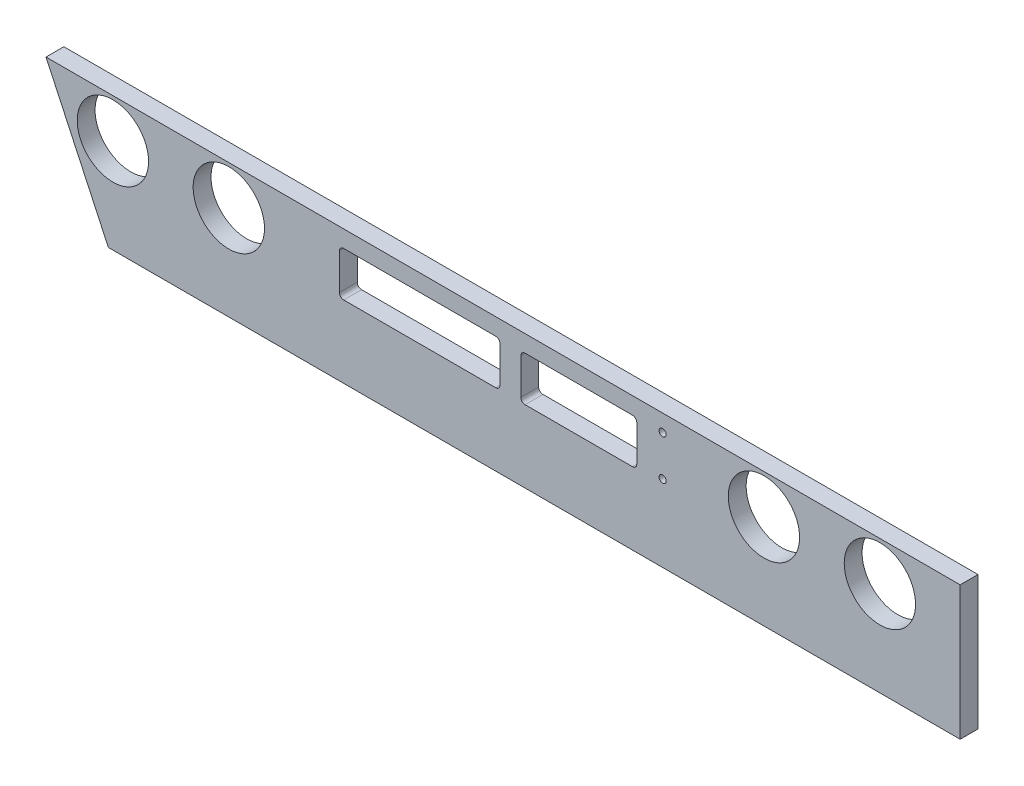
SolidWorks part; units mm, degrees
ref_plane "front" through (0, 0, 0) normal (0, 0, 1) x (1, 0, 0)
ref_plane "top" through (0, 0, 0) normal (0, 1, 0) x (1, 0, 0)
ref_plane "right" through (0, 0, 0) normal (1, 0, 0) x (0, 0, -1)
sketch "Sketch1" plane through (0, 0, 0) normal (0, 0, 1) x (1, 0, 0)
  line L0 (0, 0) -> (0, -90.9256) construction
  line L1 (-165.1, 23.8125) -> (165.1, 23.8125)
  line L2 (-165.1, 23.8125) -> (-165.1, -23.8125)
  line L3 (-165.1, -23.8125) -> (165.1, -23.8125)
  line L4 (165.1, 23.8125) -> (165.1, -23.8125)
  line L6 (-54.356, 17.78) -> (-0.254, 17.78)
  line L7 (-55.88, 16.256) -> (-55.88, 3.429)
  line L8 (-54.356, 1.905) -> (-0.254, 1.905)
  line L9 (1.27, 16.256) -> (1.27, 3.429)
  line L10 (10.2235, 17.78) -> (48.4505, 17.78)
  line L11 (8.6995, 16.256) -> (8.6995, 3.429)
  line L12 (10.2235, 1.905) -> (48.4505, 1.905)
  line L13 (49.9745, 16.256) -> (49.9745, 3.429)
  circle A0 centre (-136.525, 9.8425) radius 12.7
  circle A1 centre (-95.25, 9.8425) radius 12.7
  circle A2 centre (95.25, 9.8425) radius 12.7
  circle A3 centre (136.525, 9.8425) radius 12.7
  arc A4 (-54.356, 17.78) -> (-55.88, 16.256) centre (-54.356, 16.256) ccw
  arc A5 (-55.88, 3.429) -> (-54.356, 1.905) centre (-54.356, 3.429) ccw
  arc A6 (-0.254, 1.905) -> (1.27, 3.429) centre (-0.254, 3.429) ccw
  arc A7 (-0.254, 17.78) -> (1.27, 16.256) centre (-0.254, 16.256) cw
  arc A8 (10.2235, 17.78) -> (8.6995, 16.256) centre (10.2235, 16.256) ccw
  arc A9 (8.6995, 3.429) -> (10.2235, 1.905) centre (10.2235, 3.429) ccw
  arc A10 (48.4505, 1.905) -> (49.9745, 3.429) centre (48.4505, 3.429) ccw
  arc A11 (48.4505, 17.78) -> (49.9745, 16.256) centre (48.4505, 16.256) cw
  circle A12 centre (59.182, 17.7673) radius 1.27
  circle A13 centre (59.182, 3.4671) radius 1.27
  point P4 (0, 23.8125)
  point P5 (-165.1, 0)
  point P25 (-27.305, 17.78)
  point P26 (29.337, 17.78)
  point P27 (-55.88, 9.8425)
  point P30 (-55.88, 17.78)
  point P35 (1.27, 1.905)
  point P38 (1.27, 17.78)
  point P41 (8.6995, 17.78)
  point P48 (49.9745, 17.78)
  dimension "D5" = 25.4
  dimension "D12" = 1.524
  dimension "D13" = 27.2796
  dimension "D14" = 14.3002
  dimension "D15" = 36.068
  dimension "D16" = 2.54
  dimension "D1" = 330.2
  dimension "D2" = 47.625
  dimension "D3" = 136.525
  dimension "D4" = 95.25
  dimension "D6" = 33.655
  dimension "D7" = 57.15
  dimension "D8" = 15.875
  dimension "D9" = 41.275
  dimension "D10" = 27.305
  dimension "D11" = 29.337
extrude "Extrude1" add sketch "Sketch1" along normal blind 6.35
sketch "Sketch2" plane through (0, 0, 0) normal (0, 0, 1) x (1, 0, 0)
  line L2 (-167.7735, 39.7592) -> (-167.7735, -38.1488)
  line L3 (-167.7735, -38.1488) -> (-131.4448, -38.1488)
  line L4 (-165.1, -23.8125) -> (165.1, -23.8125) construction
  line L6 (-167.7735, 39.7592) -> (-131.4448, -38.1488)
  line L7 (165.1, 23.8125) -> (-165.1, 23.8125) construction
  line L8 (-165.1, 23.8125) -> (-165.1, -23.8125) construction
  point P3 (-138.1298, -23.8125)
  point P4 (-160.3375, 23.8125)
  dimension "D1" = 4.7625
  dimension "D2" = 26.9702
  dimension "D3" = 25
extrude "Cut-Extrude1" cut sketch "Sketch2" along normal through all
